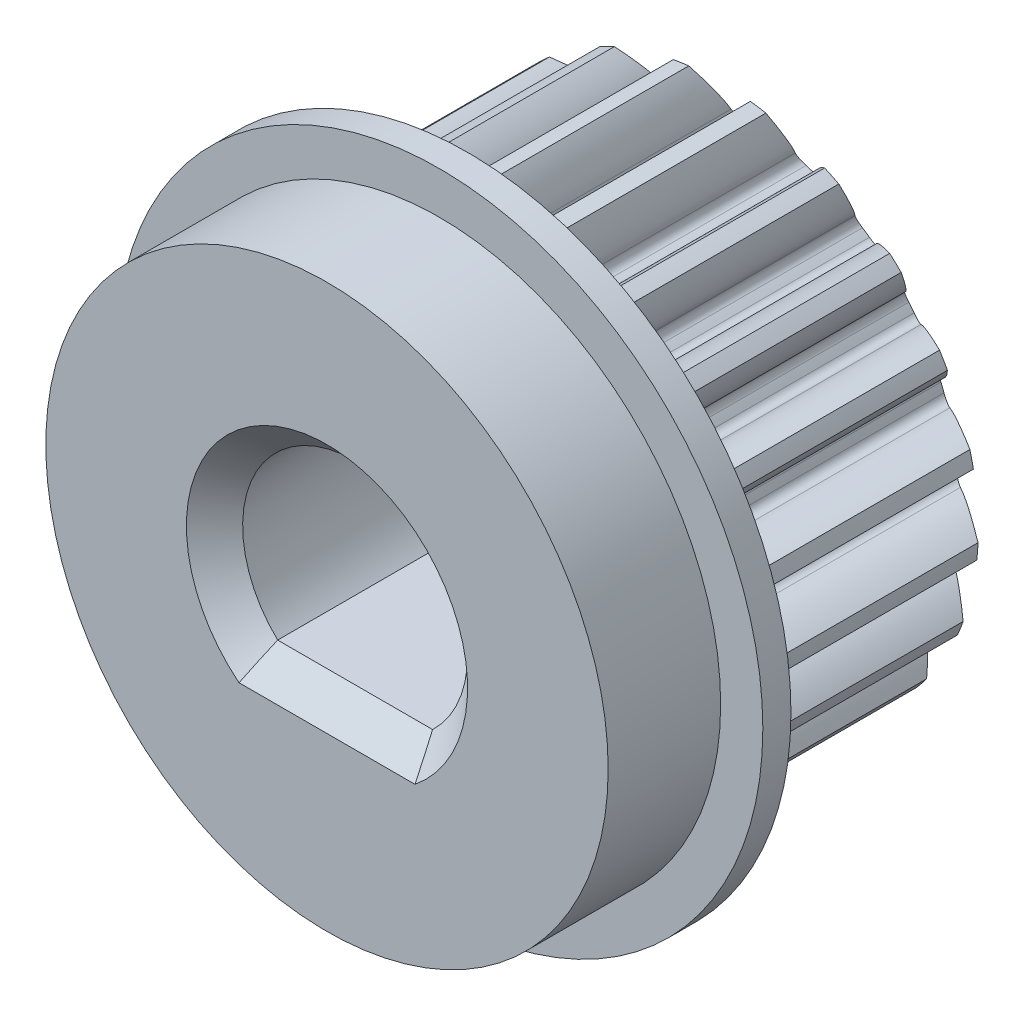
SolidWorks part; units mm, degrees
ref_plane "Front Plane" through (0, 0, 0) normal (0, 0, 1) x (1, 0, 0)
ref_plane "Top Plane" through (0, 0, 0) normal (0, 1, 0) x (1, 0, 0)
ref_plane "Right Plane" through (0, 0, 0) normal (1, 0, 0) x (0, 0, -1)
ref_axis "Axis1" through (0, 0, -88.99) along (0, 0, 1)
sketch "Sketch1" plane through (0, 0, 0) normal (0, 0, 1) x (1, 0, 0)
  circle A0 centre (0, 0) radius 9.2
  dimension "D1" = 18.4
extrude "LaShenA" add sketch "Sketch1" along normal blind 10
sketch "SketchA" plane through (0, 0, 10) normal (0, 0, 1) x (1, 0, 0)
  line L0 (0, 0) -> (0, 9.2) construction
  arc A0 (0.1502, 7.3985) -> (-0.1502, 7.3985) centre (0, 0) ccw
  arc A1 (1.4402, 9.5361) -> (-1.4402, 9.5361) centre (0, 0) ccw
  arc A2 (-0.1502, 7.3985) -> (-0.4598, 7.6841) centre (-0.1563, 7.7024) cw
  arc A3 (0.4598, 7.6841) -> (0.1502, 7.3985) centre (0.1563, 7.7024) cw
  circle A4 centre (0, 0) radius 7.8934 construction
  circle A5 centre (0, 0) radius 9.2 construction
  circle A6 centre (0, 0) radius 7.4 construction
  circle A7 centre (0, 0) radius 8.4 construction
  spline S0 degree 3 poles (0.4598, 7.6841) (0.4637, 7.7496) (0.4664, 7.8384) (0.4807, 7.9372) (0.4906, 7.9832) (0.4994, 8.0195) (0.5106, 8.0612) (0.5246, 8.1081) (0.5417, 8.16) (0.5621, 8.2169) (0.5861, 8.2786) (0.6139, 8.3449) (0.646, 8.4157) (0.6824, 8.4908) (0.7235, 8.5699) (0.7695, 8.653) (0.8207, 8.7397) (0.8772, 8.8299) (0.9394, 8.9234) (1.0073, 9.0198) (1.0813, 9.119) (1.1615, 9.2207) (1.2793, 9.3622) (1.374, 9.4667) (1.4402, 9.5361) knots 0.123319 0.123319 0.123319 0.123319 0.203409 0.232856 0.245818 0.261137 0.278814 0.298847 0.321236 0.345983 0.373086 0.402547 0.434364 0.468537 0.505068 0.543956 0.5852 0.628801 0.674759 0.723074 0.773745 0.826774 0.882159 1 1 1 1
  spline S1 degree 3 poles (-0.4598, 7.6841) (-0.4637, 7.7496) (-0.4664, 7.8384) (-0.4807, 7.9372) (-0.4906, 7.9832) (-0.4994, 8.0195) (-0.5106, 8.0612) (-0.5246, 8.1081) (-0.5417, 8.16) (-0.5621, 8.2169) (-0.5861, 8.2786) (-0.6139, 8.3449) (-0.646, 8.4157) (-0.6824, 8.4908) (-0.7235, 8.5699) (-0.7695, 8.653) (-0.8207, 8.7397) (-0.8772, 8.8299) (-0.9394, 8.9234) (-1.0073, 9.0198) (-1.0813, 9.119) (-1.1615, 9.2207) (-1.2793, 9.3622) (-1.374, 9.4667) (-1.4402, 9.5361) knots 0.123319 0.123319 0.123319 0.123319 0.203409 0.232856 0.245818 0.261137 0.278814 0.298847 0.321236 0.345983 0.373086 0.402547 0.434364 0.468537 0.505068 0.543956 0.5852 0.628801 0.674759 0.723074 0.773745 0.826774 0.882159 1 1 1 1
  dimension "D1" = 0.304
  dimension "Db" = 15.7868
  dimension "Da" = 18.4
  dimension "Df" = 14.8
  dimension "Dn" = 16.8
extrude "Cut-ExtrudeA" cut sketch "SketchA" against normal blind 10
pattern_circular "www.KYTool.cn" count 21 over 360 about axis through (0, 0, -88.99) along (0, 0, 1) of "Cut-ExtrudeA"
sketch "Sketch3" plane through (0, 0, 10) normal (0, 0, 1) x (1, 0, 0)
  circle A0 centre (0, 0) radius 11.5
  dimension "D1" = 23
extrude "Boss-Extrude2" add sketch "Sketch3" along normal blind 1
sketch "Sketch4" plane through (0, 0, 11) normal (0, 0, 1) x (1, 0, 0)
  circle A0 centre (0, 0) radius 10
  dimension "D1" = 20
extrude "Boss-Extrude3" add sketch "Sketch4" along normal blind 4
sketch "Sketch5" plane through (0, 0, 0) normal (0, 0, -1) x (-1, 0, 0)
  line L0 (2.755, -2.9) -> (-2.755, -2.9)
  line L1 (0, 4) -> (-12.8018, 4) construction
  arc A0 (2.755, -2.9) -> (-2.755, -2.9) centre (0, 0) ccw
  dimension "D1" = 8
  dimension "D2" = 6.9
extrude "Cut-Extrude2" cut sketch "Sketch5" against normal through all
chamfer "Chamfer1" distance 1 angle 45 2 edges at (0, -2.9, 15) (0, 4, 15)
sketch "Sketch15" plane through (0, 0, 0) normal (0, 1, 0) x (1, 0, 0)
  line L0 (9.2, 0) -> (7.4, 0)
  line L1 (7.4, 0) -> (9.2, -1.0392)
  line L2 (9.2, -1.0392) -> (9.2, 0)
  line L4 (2.755, 0) -> (-2.755, 0) construction
  line L5 (0, 0) -> (0, -16.5026) construction
  dimension "D1" = 30
  dimension "D2" = 1.8
  dimension "D3" = 9.2
revolve "Cut-Revolve5" cut sketch "Sketch15" angle 360 about L5
